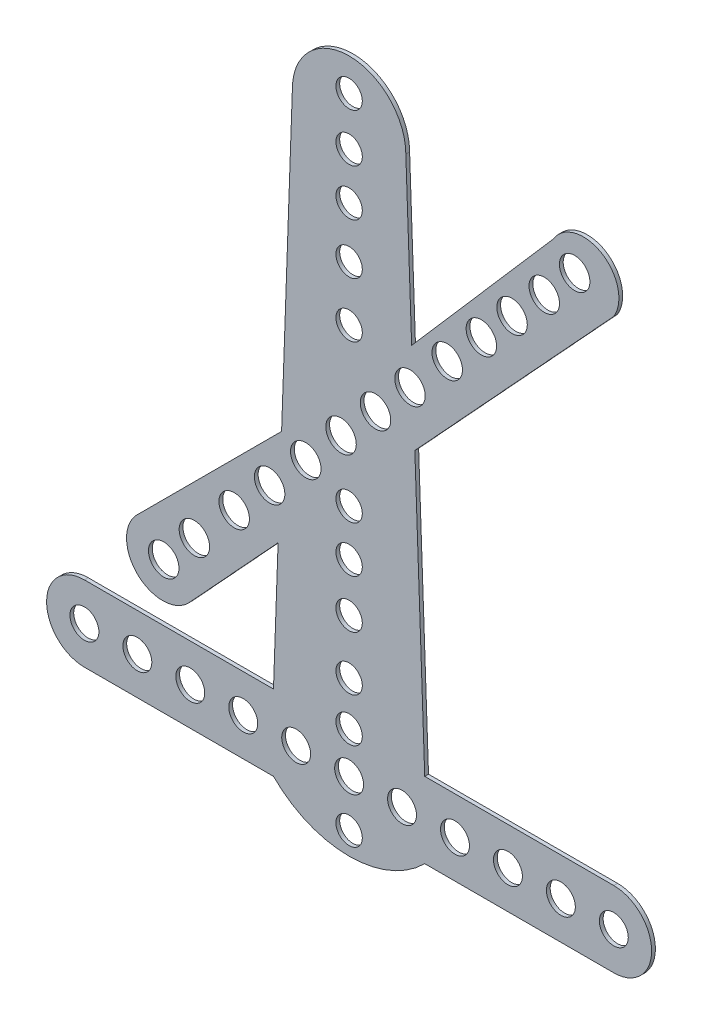
SolidWorks part; units mm, degrees
ref_plane "Front Plane" through (0, 0, 0) normal (0, 0, 1) x (1, 0, 0)
ref_plane "Top Plane" through (0, 0, 0) normal (0, 1, 0) x (1, 0, 0)
ref_plane "Right Plane" through (0, 0, 0) normal (1, 0, 0) x (0, 0, -1)
sketch "Sketch1" plane through (0, 0, 0) normal (0, 0, 1) x (1, 0, 0)
  line L0 (-75, 383.908) -> (-89.272, -15.7088)
  line L2 (-93.9056, -145.4477) -> (-100, -316.092)
  line L7 (100, -416.092) -> (350, -416.092)
  line L8 (-100, -416.092) -> (-350, -416.092)
  line L9 (0, 36.7816) -> (0, 73.5632)
  line L10 (-350, -316.092) -> (-100, -316.092)
  line L15 (-282.5665, -209.0033) -> (-89.272, -15.7088)
  line L16 (-210.3836, -271.6801) -> (-93.9056, -145.4477)
  line L17 (100, -316.092) -> (350, -316.092)
  line L18 (86.9072, 50.507) -> (100, -316.092)
  line L19 (75, 383.908) -> (82.6855, 168.7127)
  line L20 (86.9072, 50.507) -> (350, 335.6322)
  line L21 (82.6855, 168.7127) -> (269.6919, 383.908)
  arc A0 (-75, 383.908) -> (75, 383.908) centre (0, 383.908) cw
  arc A1 (269.6919, 383.908) -> (350, 335.6322) centre (309.8459, 359.7701) cw
  arc A2 (-350, -316.092) -> (-350, -416.092) centre (-350, -366.092) ccw
  arc A3 (350, -316.092) -> (350, -416.092) centre (350, -366.092) cw
  arc A4 (-100, -416.092) -> (100, -416.092) centre (0, -316.092) ccw
  arc A5 (-282.5665, -209.0033) -> (-210.3836, -271.6801) centre (-246.4751, -240.3417) ccw
  point P6 (0, 0)
  point P10 (0, 383.908)
  point P13 (0, -416.092)
  dimension "D2" = 150
  dimension "D3" = 200
  dimension "D4" = 250
  dimension "D5" = 250
extrude "Boss-Extrude2" add sketch "Sketch1" along normal blind 5
sketch "Sketch2" plane through (0, 0, 5) normal (0, 0, 1) x (1, 0, 0)
  circle A1 centre (-280, -366.092) radius 19.1277
  circle A2 centre (-210, -366.092) radius 19.1277
  circle A14 centre (-350, -366.092) radius 19.1277
  circle A15 centre (-140, -366.092) radius 19.1277
  circle A16 centre (-70, -366.092) radius 19.1277
  circle A17 centre (0, -366.092) radius 19.1277
  circle A18 centre (70, -366.092) radius 19.1277
  circle A19 centre (140, -366.092) radius 19.1277
  circle A20 centre (210, -366.092) radius 19.1277
  circle A21 centre (280, -366.092) radius 19.1277
  circle A22 centre (350, -366.092) radius 19.1277
  circle A24 centre (0, 415.8485) radius 17.4494
  circle A25 centre (0, 352.1033) radius 17.4494
  circle A26 centre (0, 290.3578) radius 17.4494
  circle A27 centre (0, 223.2231) radius 17.4494
  circle A28 centre (0, 150.5905) radius 17.4494
  circle A30 centre (0, -56.6065) radius 17.4494
  circle A31 centre (0, -117.8531) radius 17.4494
  circle A32 centre (0, -181.8426) radius 17.4494
  circle A33 centre (0, -253.6356) radius 17.4494
  circle A35 centre (0, -311.755) radius 17.4494
  circle A36 centre (0, -427.951) radius 17.4494
  circle A38 centre (-245.1289, -240.2994) radius 20.1495
  circle A39 centre (-204.5794, -195.4709) radius 20.1495
  circle A40 centre (-151.9341, -137.2703) radius 20.1495
  circle A41 centre (-105.1289, -85.5259) radius 20.1495
  circle A42 centre (-57.3021, -32.6522) radius 20.1495
  circle A43 centre (-10.671, 18.8996) radius 20.1495
  circle A44 centre (34.8711, 69.2476) radius 20.1495
  circle A45 centre (80.4979, 119.6891) radius 20.1495
  circle A46 centre (129.747, 174.1352) radius 20.1495
  circle A47 centre (174.8711, 224.0211) radius 20.1495
  circle A48 centre (215.4415, 268.8726) radius 20.1495
  circle A49 centre (258.0521, 314.4191) radius 20.1495
  circle A50 centre (298.227, 359.415) radius 20.1495
  dimension "D1" = 11
extrude "Cut-Extrude1" cut sketch "Sketch2" against normal blind 60
